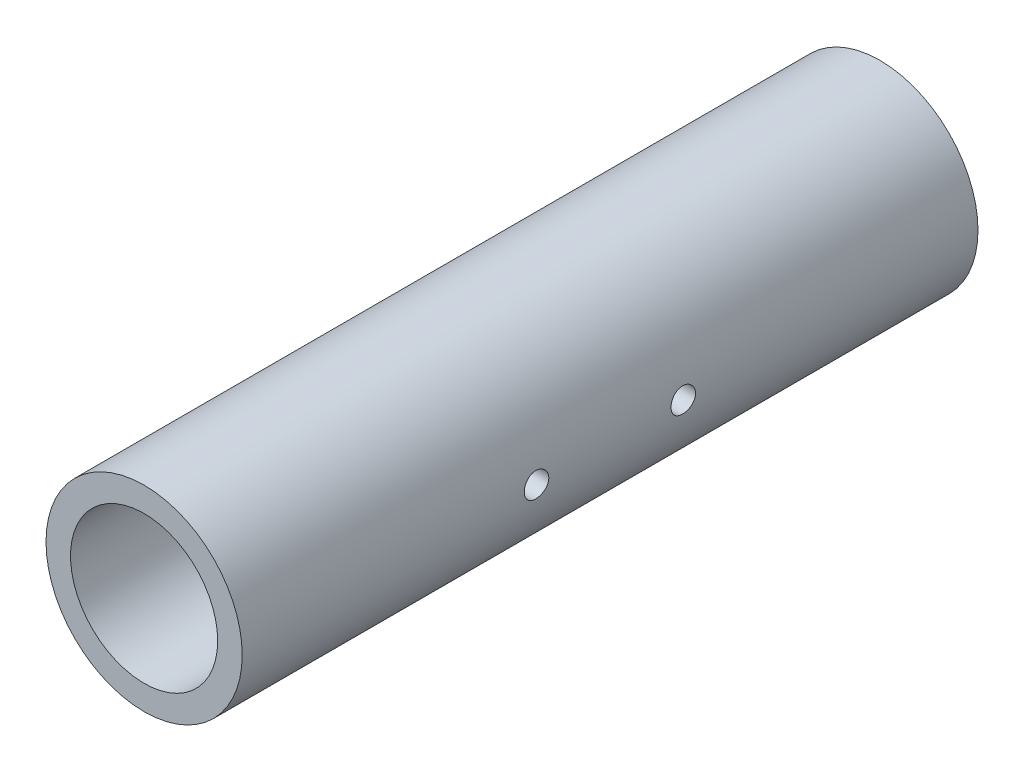
SolidWorks part; units mm, degrees
ref_plane "Front Plane" through (0, 0, 0) normal (0, 0, 1) x (1, 0, 0)
ref_plane "Top Plane" through (0, 0, 0) normal (0, 1, 0) x (1, 0, 0)
ref_plane "Right Plane" through (0, 0, 0) normal (1, 0, 0) x (0, 0, -1)
sketch "Sketch1" plane through (0, 0, 0) normal (0, 0, 1) x (1, 0, 0)
  circle A0 centre (0, 0) radius 20
  dimension "D1" = 40
extrude "Boss-Extrude1" add sketch "Sketch1" along normal blind 150
sketch "Sketch2" plane through (0, 0, 150) normal (0, 0, 1) x (1, 0, 0)
  circle A0 centre (0, 0) radius 15
  dimension "D1" = 30
extrude "Cut-Extrude1" cut sketch "Sketch2" against normal blind 150
sketch "Sketch3" plane through (0, 0, 0) normal (1, 0, 0) x (0, 0, -1)
  line L0 (-75, 36.3528) -> (-75, -33.2334) construction
  line L1 (-90, 0) -> (-60.0813, 0) construction
  line L2 (0, 0) -> (-150, 0) construction
  line L3 (-150, 20) -> (-150, -20) construction
  circle A0 centre (-90, 0) radius 2.5
  circle A1 centre (-60.0813, 0) radius 2.5
  point P4 (-75, 1.5597)
  dimension "D3" = 5
  dimension "D4" = 5
  dimension "D1" = 15
  dimension "D2" = 15
  dimension "D5" = 0
extrude "Cut-Extrude2" cut sketch "Sketch3" against normal through all both and the other way through all
